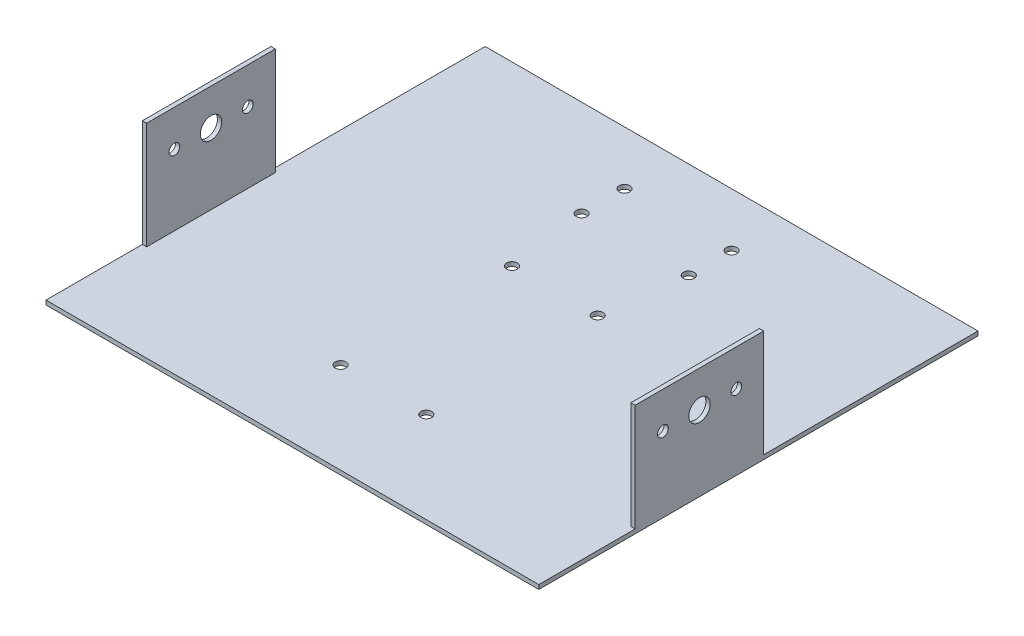
SolidWorks part; units mm, degrees
ref_plane "Front Plane" through (0, 0, 0) normal (0, 0, 1) x (1, 0, 0)
ref_plane "Top Plane" through (0, 0, 0) normal (0, 1, 0) x (1, 0, 0)
ref_plane "Right Plane" through (0, 0, 0) normal (1, 0, 0) x (0, 0, -1)
sketch "Sketch1" plane through (0, 0, 0) normal (0, 1, 0) x (1, 0, 0)
  line L0 (115, 50) -> (115, 80)
  line L1 (115, -50) -> (115, -75)
  line L2 (115, 50) -> (115, -50)
  line L4 (-115, 50) -> (-115, -50)
  line L5 (115, 50) -> (-115, -50) construction
  line L6 (115, -50) -> (-115, 50) construction
  line L7 (-115, 50) -> (-115, 80)
  line L8 (-115, 80) -> (115, 80)
  line L9 (-115, -75) -> (115, -75)
  line L10 (-115, -75) -> (-115, -50)
  point P0 (0, 0)
extrude "Boss-Extrude1" add sketch "Sketch1" along normal blind 2
sketch "Sketch2" plane through (0, 2, 0) normal (0, 1, 0) x (1, 0, 0)
  line L0 (-115, 80) -> (-115, -75) construction
  line L1 (-113, -30) -> (-115, -30)
  line L2 (-113, -30) -> (-113, 30)
  line L3 (-113, 30) -> (-115, 30)
  line L4 (0, 0) -> (0, 17.7338) construction
  line L5 (115, 30) -> (115, -30)
  line L6 (113, 30) -> (115, 30)
  line L7 (-115, 30) -> (-115, -30)
  line L8 (113, -30) -> (113, 30)
  line L9 (113, -30) -> (115, -30)
  point P0 (-115, 2.5)
  point P14 (115, 2.5)
extrude "Boss-Extrude2" add sketch "Sketch2" along normal blind 50
sketch "Sketch6" plane through (0, 2, 0) normal (0, 1, 0) x (1, 0, 0)
  line L0 (0, 80) -> (-20, 80) construction
  line L1 (115, 80) -> (-115, 80) construction
  line L2 (0, 80) -> (20, 80) construction
  line L3 (-20, 80) -> (-20, 47.5) construction
  line L4 (20, 80) -> (20, 47.5) construction
  circle A0 centre (-20, 47.5) radius 2.5
  circle A1 centre (20, 47.5) radius 2.5
extrude "Cut-Extrude3" cut sketch "Sketch6" against normal blind 20
sketch "Sketch8" plane through (0, 2, 0) normal (0, 1, 0) x (1, 0, 0)
  circle A0 centre (-20, -32.5) radius 2.5
  circle A1 centre (20, -32.5) radius 2.5
extrude "Cut-Extrude5" cut sketch "Sketch8" against normal blind 10
sketch "Sketch9" plane through (0, 2, 0) normal (0, 1, 0) x (1, 0, 0)
  line L0 (-115, 80) -> (-115, 130)
  line L1 (115, 80) -> (115, 130)
  line L2 (115, 130) -> (-115, 130)
  line L3 (-115, 80) -> (115, 80)
extrude "Boss-Extrude3" add sketch "Sketch9" against normal blind 2
sketch "Sketch10" plane through (0, 2, 0) normal (0, 1, 0) x (1, 0, 0)
  line L0 (0, 130) -> (-25, 130) construction
  line L1 (115, 130) -> (-115, 130) construction
  line L2 (-25, 130) -> (-25, 105) construction
  line L3 (-25, 105) -> (-25, 85) construction
  line L5 (0, 130) -> (0, 116.6383) construction
  circle A0 centre (-25, 85) radius 2.5
  circle A1 centre (-25, 105) radius 2.5
  circle A2 centre (25, 105) radius 2.5
  circle A3 centre (25, 85) radius 2.5
extrude "Cut-Extrude6" cut sketch "Sketch10" against normal blind 16
sketch "Sketch12" plane through (-115, 0, 0) normal (-1, 0, 0) x (0, 0, 1)
  circle A0 centre (0, 35.0514) radius 5
extrude "Cut-Extrude7" cut sketch "Sketch12" against normal blind 242
sketch "Sketch15" plane through (-115, 0, 0) normal (-1, 0, 0) x (0, 0, 1)
  circle A0 centre (-17.2237, 35) radius 2.5
  circle A1 centre (17.0639, 35) radius 2.5
extrude "Cut-Extrude8" cut sketch "Sketch15" against normal blind 242
